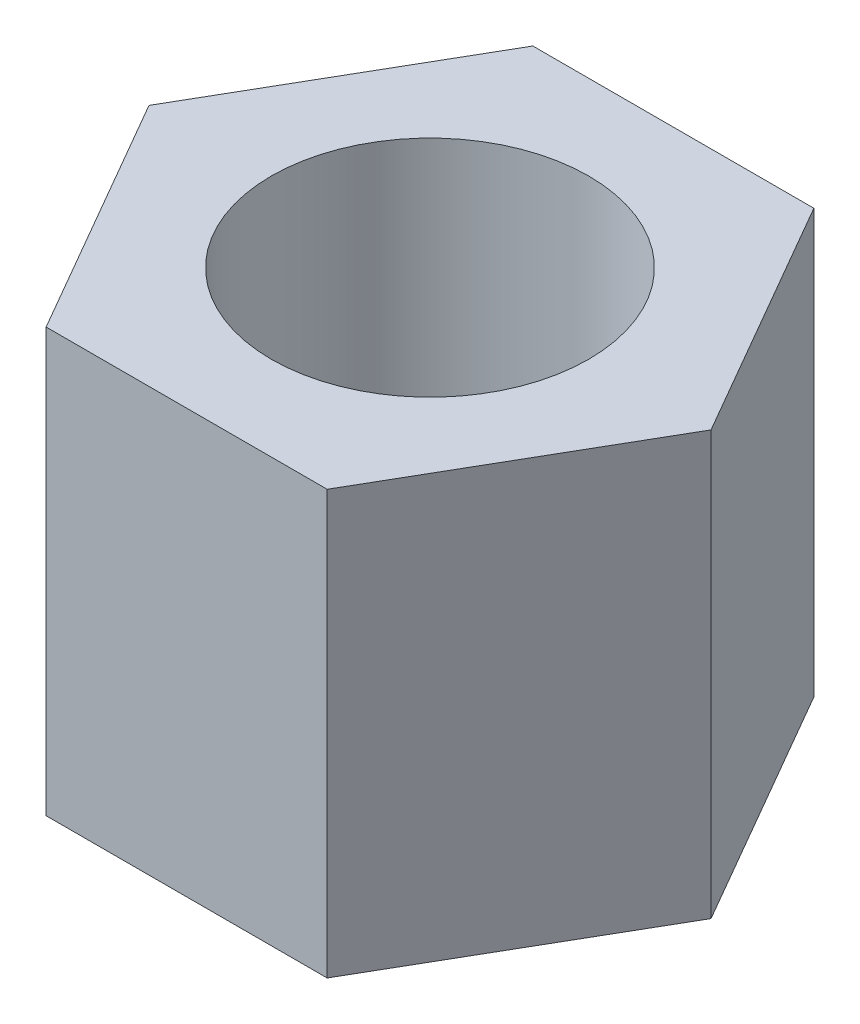
SolidWorks part; units mm, degrees
ref_plane "Front" through (0, 0, 0) normal (0, 0, 1) x (1, 0, 0)
ref_plane "Top" through (0, 0, 0) normal (0, 1, 0) x (1, 0, 0)
ref_plane "Right" through (0, 0, 0) normal (1, 0, 0) x (0, 0, -1)
sketch "草图1" plane through (0, 0, 0) normal (0, 1, 0) x (1, 0, 0)
  line L1 (-1.3279, 2.3) -> (-2.6558, 0)
  line L2 (-2.6558, 0) -> (-1.3279, -2.3)
  line L3 (-1.3279, -2.3) -> (1.3279, -2.3)
  line L4 (1.3279, -2.3) -> (2.6558, 0)
  line L5 (2.6558, 0) -> (1.3279, 2.3)
  line L6 (1.3279, 2.3) -> (-1.3279, 2.3)
  circle A0 centre (0, 0) radius 2.3 construction
  circle A1 centre (0, 0) radius 1.5 construction
  dimension "D2" = 3
  dimension "D1" = 4.6
extrude "凸台-拉伸1" add sketch "草图1" along normal blind 4
sketch "草图3" plane through (0, 4, 0) normal (0, 1, 0) x (1, 0, 0)
  circle A0 centre (0, 0) radius 1.5
  dimension "D1" = 3
sketch "草图4" plane through (0, 0, 0) normal (0, -1, 0) x (1, 0, 0)
  circle A0 centre (0, 0) radius 1.5
  dimension "D1" = 3
extrude "切除-拉伸1" cut sketch "草图4" against normal up to surface (4 mm away) up to face at (0, 4, 0)
cosmetic thread "装饰螺纹线1"
ref_plane "基准面1" through (0, 2, 0) normal (0, 1, 0) x (1, 0, 0)
